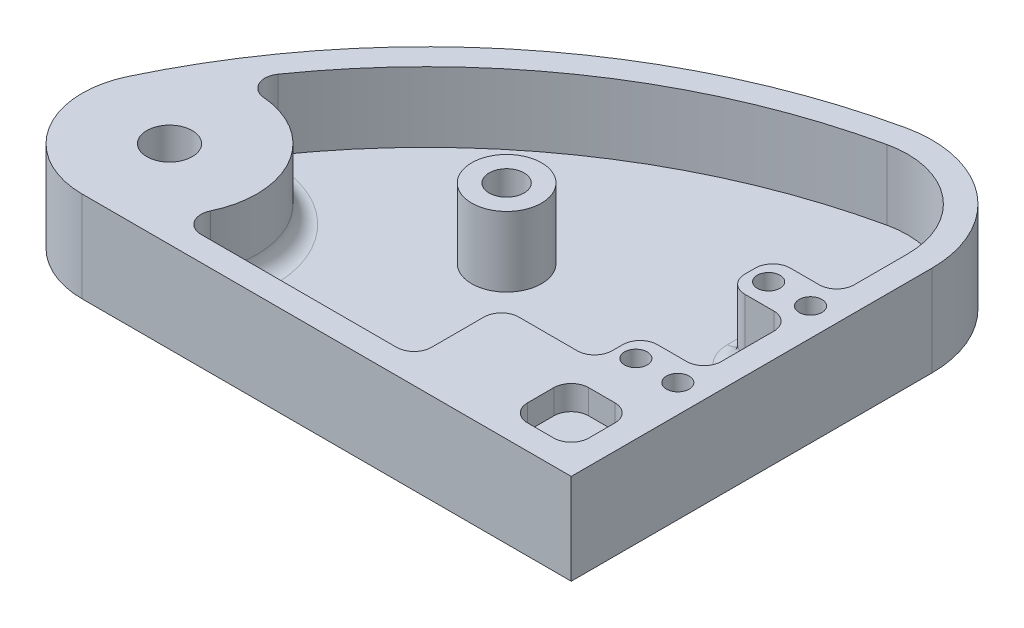
SolidWorks part; units mm, degrees
ref_plane "Front Plane" through (0, 0, 0) normal (0, 0, 1) x (1, 0, 0)
ref_plane "Top Plane" through (0, 0, 0) normal (0, 1, 0) x (1, 0, 0)
ref_plane "Right Plane" through (0, 0, 0) normal (1, 0, 0) x (0, 0, -1)
sketch "Sketch1" plane through (0, 0, 0) normal (0, 1, 0) x (1, 0, 0)
  line L0 (0, -25) -> (140, -25)
  line L1 (140, -25) -> (140, 78.2895)
  arc A0 (-22.5806, 10.7291) -> (0, -25) centre (0, 0) ccw
  arc A1 (101.4503, 109.3029) -> (-22.5806, 10.7291) centre (140, -66.5207) ccw
  arc A2 (140, 78.2895) -> (101.4503, 109.3029) centre (108.25, 78.2895) ccw
  dimension "D1" = 50
  dimension "D2" = 360
  dimension "D3" = 63.5
  dimension "D4" = 140
extrude "Boss-Extrude1" add sketch "Sketch1" along normal blind 26
sketch "Sketch2" plane through (0, 26, 0) normal (0, 1, 0) x (1, 0, 0)
  line L2 (88, -18) -> (88, 7)
  line L3 (88, 7) -> (114.7, 7)
  line L4 (0, -18) -> (133, -18)
  line L5 (133, -18) -> (133, 78.2895)
  line L6 (17.3494, -18) -> (88, -18)
  line L7 (133, 20) -> (133, 45)
  line L8 (114.7, 7) -> (114.7, 20)
  line L9 (114.7, 20) -> (133, 20)
  line L10 (0, -25) -> (140, -25) construction
  line L11 (133, 58) -> (133, 78.2895)
  line L12 (114.7, 58) -> (133, 58)
  line L13 (114.7, 58) -> (114.7, 45)
  line L14 (114.7, 45) -> (133, 45)
  line L16 (140, -25) -> (140, 78.2895) construction
  arc A0 (17.3494, -18) -> (-7.5259, 23.8403) centre (0, 0) ccw
  arc A1 (-22.5806, 10.7291) -> (0, -25) centre (0, 0) ccw construction
  arc A6 (133, 78.2895) -> (102.9494, 102.4653) centre (108.25, 78.2895) ccw
  arc A7 (102.9494, 102.4653) -> (-16.2581, 7.725) centre (140, -66.5207) ccw
  arc A8 (133, 78.2895) -> (102.9494, 102.4653) centre (108.25, 78.2895) ccw
  arc A9 (102.9494, 102.4653) -> (-7.5259, 23.8403) centre (140, -66.5207) ccw
  dimension "D2" = 45
  dimension "D3" = 32
  dimension "D4" = 13
  dimension "D5" = 25
  dimension "D6" = 13
  dimension "D7" = 25.3
  dimension "D1" = 7
extrude "Cut-Extrude1" cut sketch "Sketch2" against normal blind 20
sketch "Sketch3" plane through (0, 26, 0) normal (0, 1, 0) x (1, 0, 0)
  line L0 (140, -25) -> (140, 78.2895) construction
  line L1 (115.5, -0.5) -> (133, -0.5)
  line L2 (115.5, -0.5) -> (115.5, -18)
  line L3 (115.5, -18) -> (133, -18)
  line L4 (133, -0.5) -> (133, -18)
  line L5 (0, -25) -> (140, -25) construction
  dimension "D1" = 17.5
  dimension "D2" = 17.5
  dimension "D3" = 7
  dimension "D4" = 7
extrude "Cut-Extrude2" cut sketch "Sketch3" against normal blind 7
fillet "Fillet1" radius 5 25 edges at (123.85, 6, -58) (115.5, 22.5, 18) (115.5, 22.5, 0.5) (133, 22.5, 0.5) (133, 22.5, 18) (88, 16, 18) (133, 16, -45) (133, 16, -20) (114.7, 16, -20) (114.7, 16, -7) (88, 16, -7) (114.7, 16, -58) (133, 16, -58) (114.7, 16, -45) (-7.5259, 16, -23.8403) (17.3494, 16, 18) (52.6747, 6, 18) (88, 6, 5.5) (101.35, 6, -7) (114.7, 6, -13.5) (123.85, 6, -20) (133, 6, -32.5) (123.85, 6, -45) (114.7, 6, -51.5) (21.489, 6, -12.7758)
hole_wizard "Hole1" positions "Sketch4" profile "Sketch5" legacy
sketch "Sketch4" plane through (0, 26, 0) normal (0, 1, 0) x (1, 0, 0)
  point P0 (0, 0)
sketch "Sketch5" plane through (0, 26, 0) normal (1, 0, 0) x (0, 0, 1)
  line L0 (0, 0) -> (0, 30)
  line L1 (0, 30) -> (6.5, 30)
  line L2 (6.5, 30) -> (6.5, 0)
  line L3 (6.5, 0) -> (0, 0)
  line L4 (0, 110) -> (0, -10) construction
  dimension "Diameter" = 13
  dimension "Depth" = 30
hole_wizard "Hole2" positions "Sketch6" profile "Sketch7" legacy
sketch "Sketch6" plane through (0, 26, 0) normal (0, 1, 0) x (1, 0, 0)
  line L0 (128, -0.5) -> (120.5, -0.5) construction
  line L1 (140, -25) -> (140, 78.2895) construction
  point P0 (120, 51.5)
  point P2 (132, 51.5)
  point P4 (120, 13.5)
  point P6 (132, 13.5)
  point P11 (0, 0)
  point P12 (0, 0)
  point P13 (0, 0)
  point P14 (0, 0)
  point P15 (133.0635, 13.5)
  point P16 (121.997, 13.5)
  point P17 (119.7, 13.5)
  point P18 (0, 0)
  point P19 (121.8241, 51.5)
  dimension "D1" = 38
  dimension "D2" = 14
  dimension "D3" = 12
  dimension "D4" = 8
sketch "Sketch7" plane through (120, 26, -51.5) normal (1, 0, 0) x (0, 0, 1)
  line L0 (0, 0) -> (0, 30)
  line L1 (0, 30) -> (3.25, 30)
  line L2 (3.25, 30) -> (3.25, 0)
  line L3 (3.25, 0) -> (0, 0)
  line L4 (0, 110) -> (0, -10) construction
  dimension "Diameter" = 6.5
  dimension "Depth" = 30
sketch "Sketch8" plane through (0, 6, 0) normal (0, 1, 0) x (1, 0, 0)
  line L0 (83, -13) -> (83, 2) construction
  line L1 (0, -25) -> (140, -25) construction
  circle A0 centre (58, 38.5) radius 10
  dimension "D1" = 20
  dimension "D2" = 63.5
  dimension "D3" = 25
extrude "Boss-Extrude2" add sketch "Sketch8" along normal blind 20
hole_wizard "Hole3" positions "Sketch9" profile "Sketch10" legacy
sketch "Sketch9" plane through (0, 26, 0) normal (0, 1, 0) x (1, 0, 0)
  point P0 (58, 38.5)
sketch "Sketch10" plane through (58, 26, -38.5) normal (1, 0, 0) x (0, 0, 1)
  line L0 (0, 0) -> (0, 30)
  line L1 (0, 30) -> (5, 30)
  line L2 (5, 30) -> (5, 0)
  line L3 (5, 0) -> (0, 0)
  line L4 (0, 110) -> (0, -10) construction
  dimension "Diameter" = 10
  dimension "Depth" = 30
